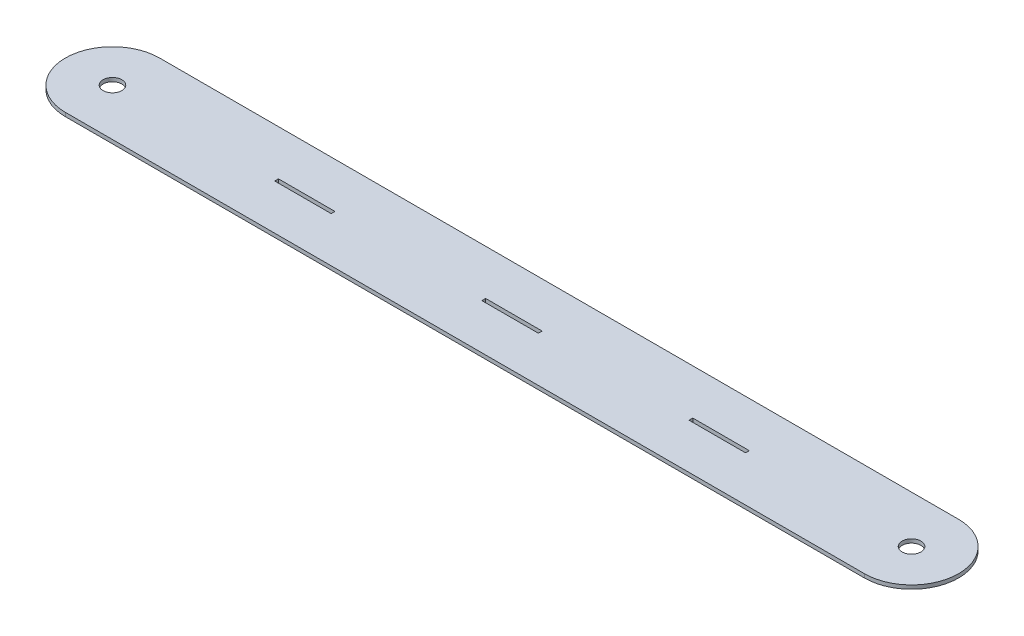
SolidWorks part; units mm, degrees
ref_plane "Front Plane" through (0, 0, 0) normal (0, 0, 1) x (1, 0, 0)
ref_plane "Top Plane" through (0, 0, 0) normal (0, 1, 0) x (1, 0, 0)
ref_plane "Right Plane" through (0, 0, 0) normal (1, 0, 0) x (0, 0, -1)
sketch "Sketch1" plane through (0, 0, 0) normal (0, 1, 0) x (1, 0, 0)
  line L0 (0, 0) -> (212.132, 0) construction
  line L1 (51.066, 0) -> (51.066, 23.4994) construction
  line L2 (43.566, -0.5) -> (58.566, -0.5)
  line L3 (0, 0) -> (212.132, 0) construction
  line L4 (0, 12.5) -> (212.132, 12.5)
  line L5 (0, -12.5) -> (212.132, -12.5)
  line L6 (43.566, -0.5) -> (43.566, 0.5)
  line L7 (43.566, 0.5) -> (58.566, 0.5)
  line L8 (58.566, -0.5) -> (58.566, 0.5)
  line L9 (43.566, -0.5) -> (58.566, 0.5) construction
  line L10 (43.566, 0.5) -> (58.566, -0.5) construction
  line L11 (98.566, -0.5) -> (113.566, -0.5)
  line L12 (98.566, -0.5) -> (98.566, 0.5)
  line L13 (98.566, 0.5) -> (113.566, 0.5)
  line L14 (113.566, -0.5) -> (113.566, 0.5)
  line L15 (98.566, -0.5) -> (113.566, 0.5) construction
  line L16 (98.566, 0.5) -> (113.566, -0.5) construction
  line L17 (153.566, -0.5) -> (168.566, -0.5)
  line L18 (153.566, -0.5) -> (153.566, 0.5)
  line L19 (153.566, 0.5) -> (168.566, 0.5)
  line L20 (168.566, -0.5) -> (168.566, 0.5)
  line L21 (153.566, -0.5) -> (168.566, 0.5) construction
  line L22 (153.566, 0.5) -> (168.566, -0.5) construction
  line L23 (51.066, 23.4994) -> (106.066, 23.4994) construction
  line L24 (106.066, 23.4994) -> (106.066, 0) construction
  line L25 (161.066, 0) -> (161.066, 23.4994) construction
  line L26 (161.066, 23.4994) -> (106.066, 23.4994) construction
  circle A0 centre (0, 0) radius 2.5
  circle A1 centre (212.132, 0) radius 2.5
  arc A2 (0, 12.5) -> (0, -12.5) centre (0, 0) ccw
  arc A3 (212.132, -12.5) -> (212.132, 12.5) centre (212.132, 0) ccw
  point P6 (51.066, 0)
  point P7 (106.066, 0)
  point P12 (106.066, 0)
  point P21 (161.066, 0)
  dimension "D3" = 5
  dimension "D1" = 212.132
  dimension "D2" = 55
  dimension "D4" = 25
  dimension "D5" = 55
  dimension "D6" = 15
  dimension "D7" = 1
extrude "Boss-Extrude1" add sketch "Sketch1" along normal blind 1
